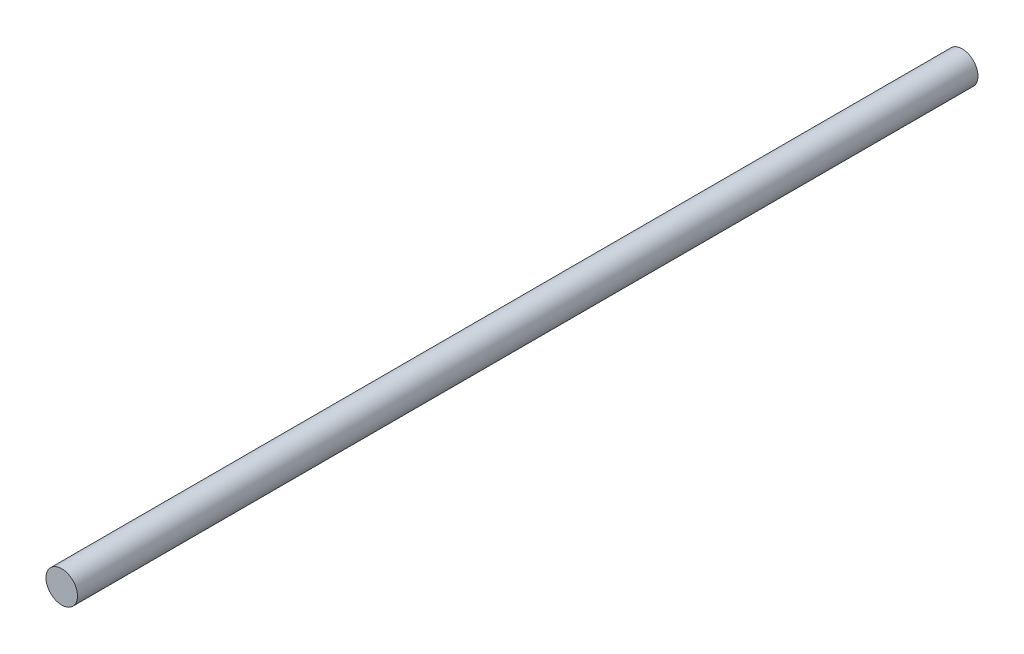
SolidWorks part; units mm, degrees
ref_plane "Front Plane" through (0, 0, 0) normal (0, 0, 1) x (1, 0, 0)
ref_plane "Top Plane" through (0, 0, 0) normal (0, 1, 0) x (1, 0, 0)
ref_plane "Right Plane" through (0, 0, 0) normal (1, 0, 0) x (0, 0, -1)
sketch "Sketch1" plane through (0, 0, 0) normal (0, 0, 1) x (1, 0, 0)
  circle A0 centre (0, 0) radius 0.7
  dimension "D1" = 1.4
extrude "Boss-Extrude1" add sketch "Sketch1" along normal blind 40
